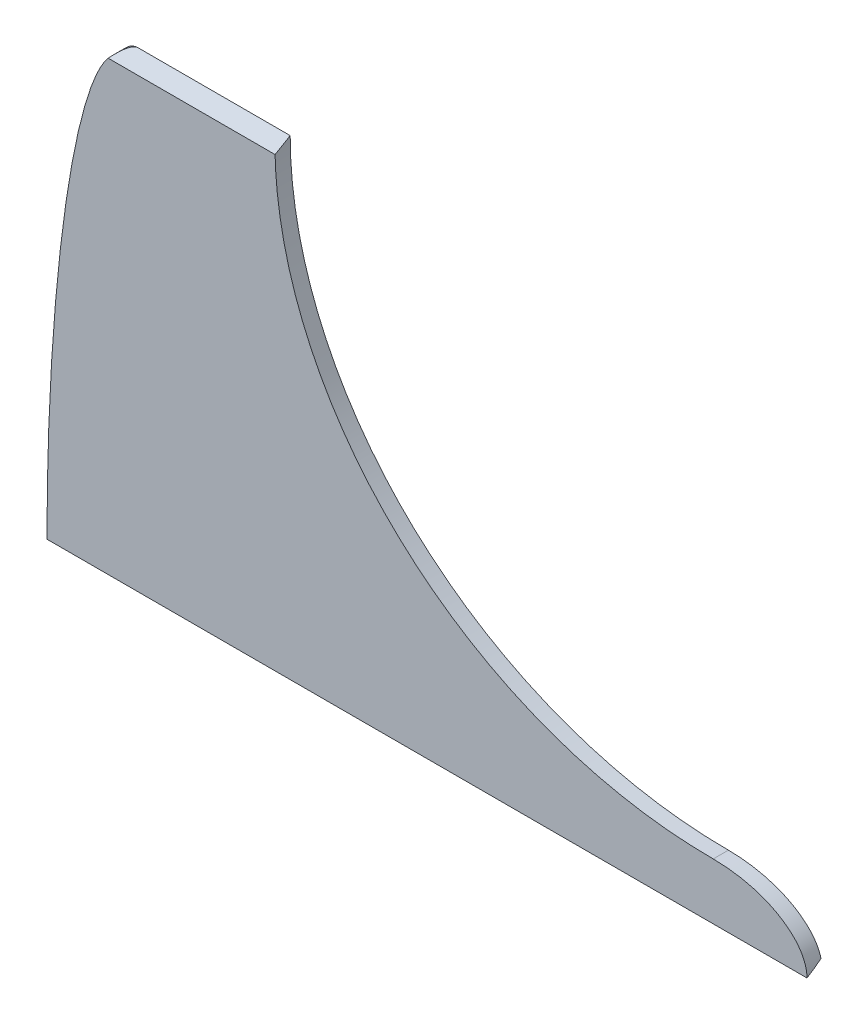
SolidWorks part; units mm, degrees
ref_plane "Front Plane" through (0, 0, 0) normal (0, 0, 1) x (1, 0, 0)
ref_plane "Top Plane" through (0, 0, 0) normal (0, 1, 0) x (1, 0, 0)
ref_plane "Right Plane" through (0, 0, 0) normal (1, 0, 0) x (0, 0, -1)
sketch "Sketch1" plane through (0, 0, 0) normal (0, 0, 1) x (1, 0, 0)
  line L0 (0, 0) -> (-114.3, 0)
  line L1 (-101.6, 0) -> (-101.6, 76.2) construction
  line L2 (-76.2, 76.2) -> (-101.6, 76.2)
  line L3 (0, 0) -> (12.7, 0)
  line L4 (-2.963, 76.2) -> (-76.2, 76.2) construction
  line L5 (-2.963, 0) -> (-2.963, 9.4005) construction
  ellipse E0 centre (-101.6, 0) end of major axis (-101.6, -76.2) minor radius 12.7 (-101.6, 76.2) -> (-114.3, 0) ccw
  ellipse E1 centre (-2.963, 76.2) end of major axis (-76.2, 76.2) minor radius 66.7995 (-76.2, 76.2) -> (-2.963, 9.4005) ccw
  ellipse E2 centre (-2.963, 0) end of major axis (-18.626, 0) minor radius 9.4005 (12.7, 0) -> (-2.963, 9.4005) ccw
  dimension "D2" = 76.2
  dimension "D1" = 76.2
  dimension "D3" = 12.7
  dimension "D4" = 114.3
  dimension "D5" = 12.7
  dimension "D6" = 73.237
  dimension "D7" = 66.7995
extrude "Boss-Extrude1" add sketch "Sketch1" along normal blind 2.54
sketch "Sketch4" plane through (0, 0, 0) normal (-1, 0, 0) x (0, 0, 1)
  line L0 (2.54, 0) -> (0, 1.4665)
  line L1 (0, 1.4665) -> (0, 0)
  line L2 (0, 0) -> (2.54, 0)
  line L4 (2.54, 0) -> (2.54, 76.2) construction
  line L5 (0, 76.2) -> (0, 0) construction
  dimension "D1" = 30
extrude "Cut-Extrude3" cut sketch "Sketch4" against normal blind 17.272 and the other way blind 121.252
sketch "Sketch5" plane through (0, 0, 0) normal (-1, 0, 0) x (0, 0, 1)
  line L0 (0, 76.2) -> (2.54, 74.7335)
  line L1 (2.54, 74.7335) -> (2.54, 76.2)
  line L2 (2.54, 76.2) -> (0, 76.2)
  dimension "D1" = 30
extrude "Cut-Extrude4" cut sketch "Sketch5" against normal blind 4.064 and the other way blind 118.458
